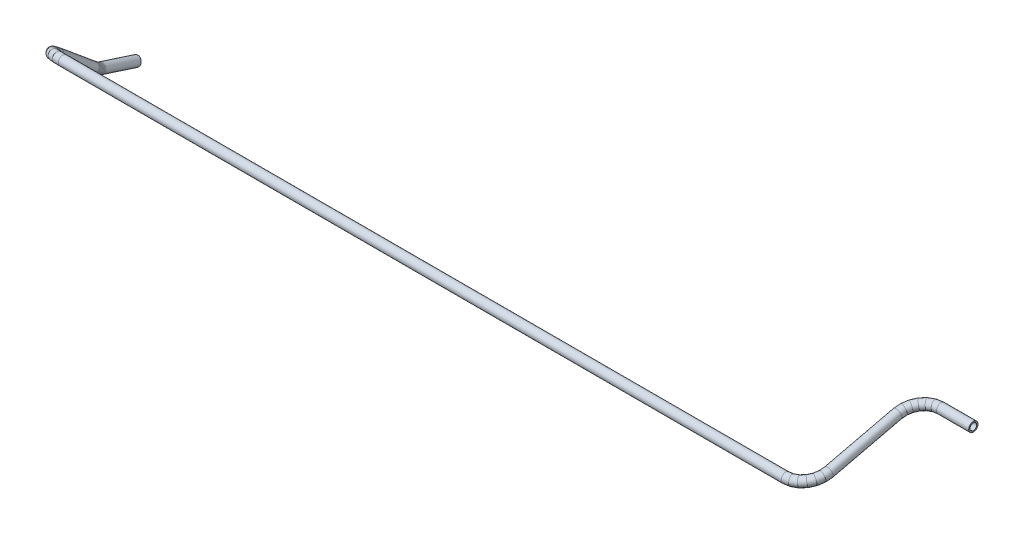
SolidWorks part; units mm, degrees
ref_plane "Front Plane" through (0, 0, 0) normal (0, 0, 1) x (1, 0, 0)
ref_plane "Top Plane" through (0, 0, 0) normal (0, 1, 0) x (1, 0, 0)
ref_plane "Right Plane" through (0, 0, 0) normal (1, 0, 0) x (0, 0, -1)
sketch3d "Path"
  line L0 (-2218.988, 62, 0) -> (-2241.188, 62, 0)
  line L1 (-2241.188, 62, 0) -> (-2245.0702, 61.8825, 0.4974)
  line L2 (-2245.0702, 61.8825, 0.4974) -> (-2248.688, 61.5381, 1.9558)
  line L3 (-2248.688, 61.5381, 1.9558) -> (-2251.7946, 60.9901, 4.2758)
  line L4 (-2251.7946, 60.9901, 4.2758) -> (-2254.1783, 60.276, 7.2992)
  line L5 (-2254.1783, 60.276, 7.2992) -> (-2255.6768, 59.4444, 10.82)
  line L6 (-2255.6768, 59.4444, 10.82) -> (-2256.188, 58.552, 14.5983)
  line L7 (-2256.188, 58.552, 14.5983) -> (-2256.188, 47.448, 61.6119)
  line L8 (-2256.188, 47.448, 61.6119) -> (-2256.6991, 46.5556, 65.3902)
  line L9 (-2256.6991, 46.5556, 65.3902) -> (-2258.1976, 45.724, 68.9111)
  line L10 (-2258.1976, 45.724, 68.9111) -> (-2260.5814, 45.0099, 71.9345)
  line L11 (-2260.5814, 45.0099, 71.9345) -> (-2263.688, 44.4619, 74.2544)
  line L12 (-2263.688, 44.4619, 74.2544) -> (-2267.3057, 44.1175, 75.7128)
  line L13 (-2267.3057, 44.1175, 75.7128) -> (-2271.188, 44, 76.2102)
  line L14 (-2271.188, 44, 76.2102) -> (-2765.0928, 44, 76.2102)
  line L15 (-2765.0928, 44, 76.2102) -> (-2768.9751, 43.6738, 75.8167)
  line L16 (-2768.9751, 43.6738, 75.8167) -> (-2772.5928, 42.7175, 74.6631)
  line L17 (-2772.5928, 42.7175, 74.6631) -> (-2775.6994, 41.1962, 72.8279)
  line L18 (-2775.6994, 41.1962, 72.8279) -> (-2778.0832, 39.2136, 70.4361)
  line L19 (-2778.0832, 39.2136, 70.4361) -> (-2779.5817, 36.9048, 67.6509)
  line L20 (-2779.5817, 36.9048, 67.6509) -> (-2780.0928, 34.4271, 64.6621)
  line L21 (-2780.0928, 34.4271, 64.6621) -> (-2780.0928, 14.1917, 40.2511)
  line L22 (-2780.0928, 14.1917, 40.2511) -> (-2780.0928, 13.612, 39.5051)
  line L23 (-2780.0928, 13.612, 39.5051) -> (-2780.0928, 13.0803, 38.7241)
  line L24 (-2780.0928, 13.0803, 38.7241) -> (-2780.0928, 12.5989, 37.9111)
  line L25 (-2780.0928, 12.5989, 37.9111) -> (-2780.0928, 12.1696, 37.0695)
  line L26 (-2780.0928, 12.1696, 37.0695) -> (-2780.0928, 11.7942, 36.2025)
  line L27 (-2780.0928, 11.7942, 36.2025) -> (-2780.0928, 11.4741, 35.3135)
  line L28 (-2780.0928, 11.4741, 35.3135) -> (-2780.0928, 3.6155, 11.1274)
ref_plane "Start Plane" through (-2218.988, 0, 0) normal (1, 0, 0) x (0, 0, -1)
sketch "Profile" plane through (-2218.988, 0, 0) normal (1, 0, 0) x (0, 0, -1)
  circle A0 centre (0, 62) radius 3.175
  circle A1 centre (0, 62) radius 2.286
sweep "Tube" add profiles "Profile" path "Path"
